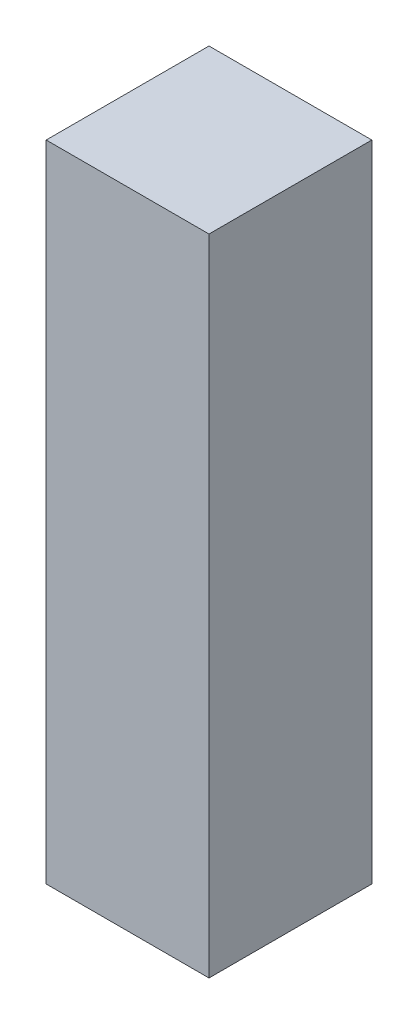
SolidWorks part; units mm, degrees
ref_plane "Front Plane" through (0, 0, 0) normal (0, 0, 1) x (1, 0, 0)
ref_plane "Top Plane" through (0, 0, 0) normal (0, 1, 0) x (1, 0, 0)
ref_plane "Right Plane" through (0, 0, 0) normal (1, 0, 0) x (0, 0, -1)
sketch "Sketch1" plane through (0, 0, 0) normal (0, 1, 0) x (1, 0, 0)
  line L1 (-150, -150) -> (150, -150)
  line L2 (-150, -150) -> (-150, 150)
  line L3 (-150, 150) -> (150, 150)
  line L4 (150, -150) -> (150, 150)
  line L5 (-150, -150) -> (150, 150) construction
  line L6 (-150, 150) -> (150, -150) construction
  point P0 (0, 0)
  dimension "D1" = 300
  dimension "D2" = 300
extrude "Boss-Extrude1" add sketch "Sketch1" along normal blind 1187.25
